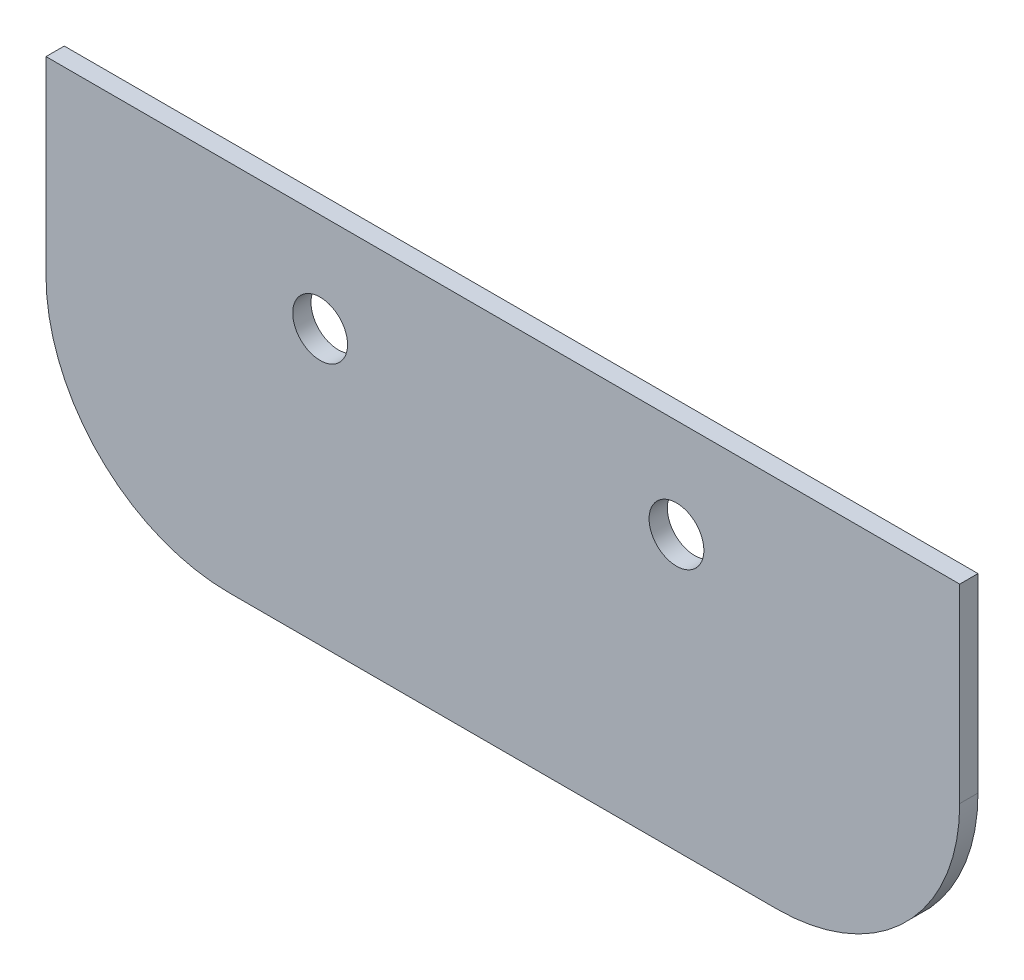
SolidWorks part; units mm, degrees
ref_plane "Front Plane" through (0, 0, 0) normal (0, 0, 1) x (1, 0, 0)
ref_plane "Top Plane" through (0, 0, 0) normal (0, 1, 0) x (1, 0, 0)
ref_plane "Right Plane" through (0, 0, 0) normal (1, 0, 0) x (0, 0, -1)
sketch "Sketch1" plane through (0, 0, 0) normal (0, 0, 1) x (1, 0, 0)
  line L0 (0, 20.4006) -> (50, 20.4006)
  line L1 (0, 0) -> (50, 0)
  line L2 (0, 0) -> (0, 20.4006)
  line L3 (50, 20.4006) -> (50, 0)
  circle A0 centre (15, 15) radius 1.5
  circle A1 centre (34.5, 15) radius 1.5
extrude "Boss-Extrude1" add sketch "Sketch1" along normal blind 1
fillet "Fillet3" radius 10 1 edges at (0, 0, 0.5)
fillet "Fillet5" radius 10 1 edges at (50, 0, 0.5)
